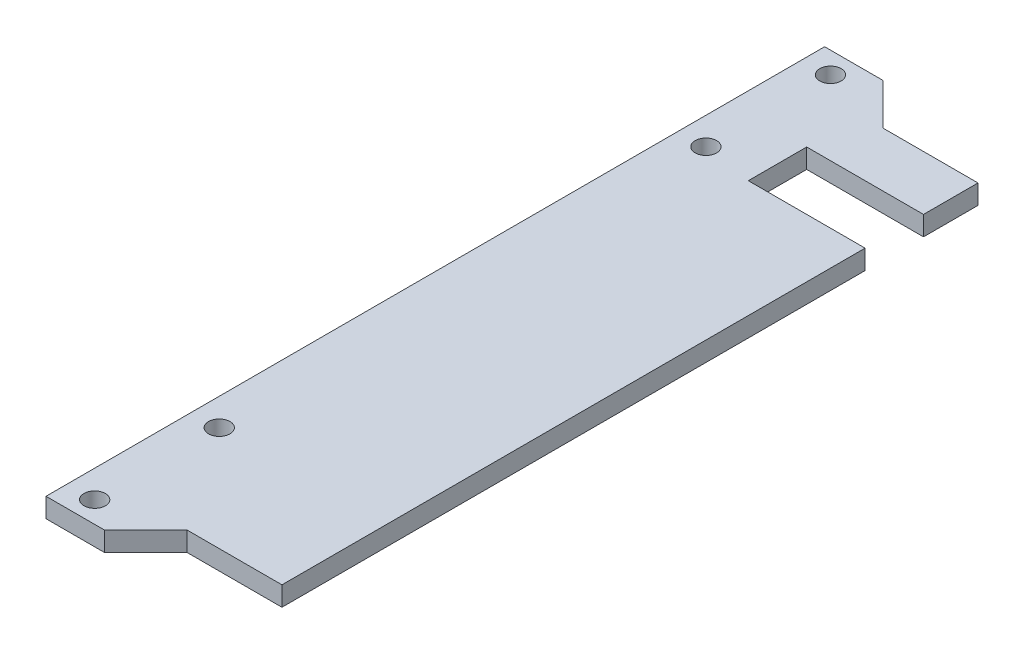
SolidWorks part; units mm, degrees
ref_plane "Plan de face" through (0, 0, 0) normal (0, 0, 1) x (1, 0, 0)
ref_plane "Plan de dessus" through (0, 0, 0) normal (0, 1, 0) x (1, 0, 0)
ref_plane "Plan de droite" through (0, 0, 0) normal (1, 0, 0) x (0, 0, -1)
sketch "Esquisse1" plane through (0, 0, 0) normal (0, 1, 0) x (1, 0, 0)
  line L1 (0, 100) -> (15, 100)
  line L2 (15, 100) -> (25.6066, 89.3934)
  line L3 (25.6066, 89.3934) -> (50, 89.3934)
  line L7 (0, 100) -> (0, -100)
  line L8 (50, -89.3934) -> (50, 89.3934)
  line L9 (-112.7395, 0) -> (145.5514, 0) construction
  line L10 (25.6066, -89.3934) -> (50, -89.3934)
  line L11 (15, -100) -> (25.6066, -89.3934)
  line L12 (0, -100) -> (15, -100)
  circle A0 centre (7, 94.5) radius 2.75
  circle A1 centre (7, 62.5) radius 2.75
  circle A2 centre (7, -62.5) radius 2.75
  circle A3 centre (7, -94.5) radius 2.75
  point P10 (50, 0)
  point P11 (0, 0)
  dimension "D6" = 5.5
  dimension "D7" = 5.5
  dimension "D1" = 200
  dimension "D2" = 45
  dimension "D3" = 50
  dimension "D4" = 15
  dimension "D5" = 15
  dimension "D8" = 7
  dimension "D9" = 62.5
  dimension "D10" = 32
extrude "Boss.-Extru.1" add sketch "Esquisse1" along normal blind 5
sketch "Esquisse2" plane through (0, 5, 0) normal (0, 1, 0) x (1, 0, 0)
  line L0 (50, 75.3934) -> (20, 75.3934)
  line L1 (50, -89.3934) -> (50, 89.3934) construction
  line L2 (20, 75.3934) -> (20, 60.3934)
  line L3 (20, 60.3934) -> (50, 60.3934)
  line L4 (50, 60.3934) -> (50, 75.3934)
  line L5 (50, 89.3934) -> (25.6066, 89.3934) construction
  dimension "D1" = 14
  dimension "D2" = 15
  dimension "D3" = 30
extrude "Enlèv. mat.-Extru.1" cut sketch "Esquisse2" against normal through all
